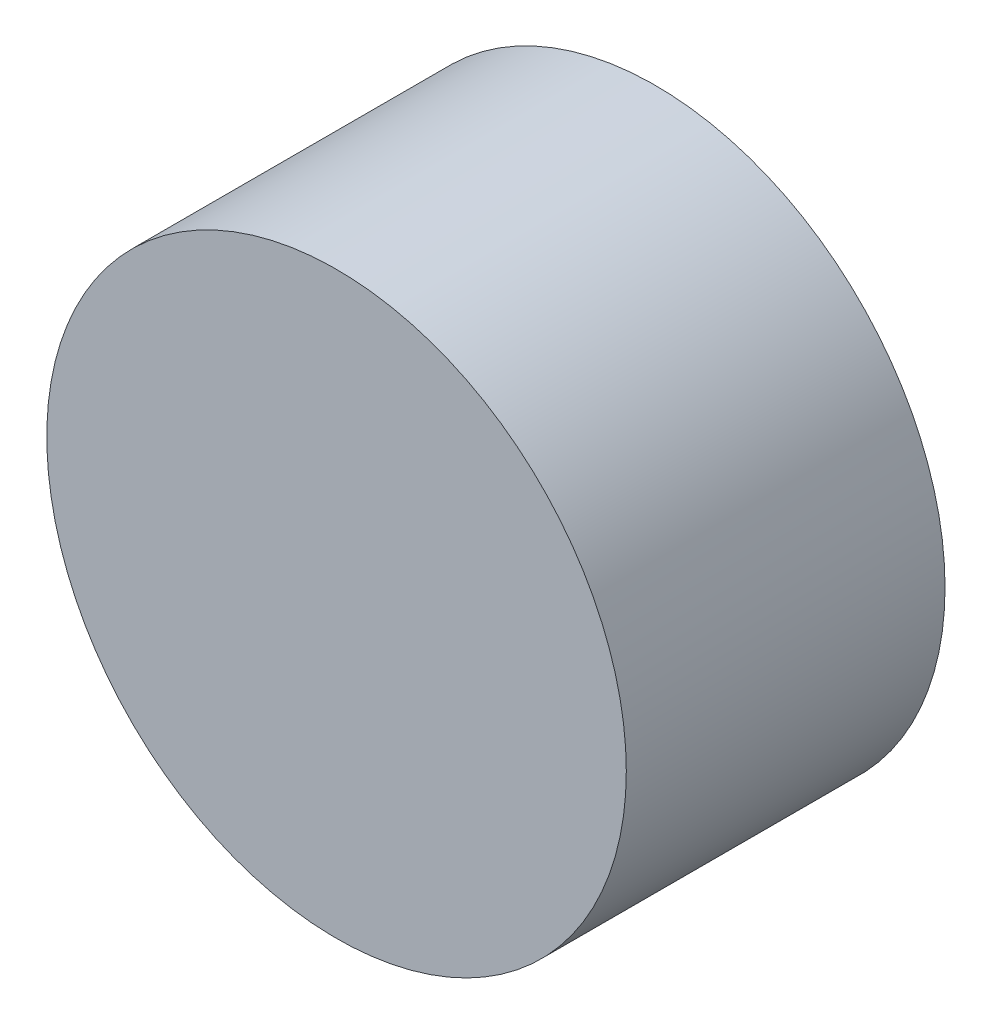
SolidWorks part; units mm, degrees
ref_plane "Front Plane" through (0, 0, 0) normal (0, 0, 1) x (1, 0, 0)
ref_plane "Top Plane" through (0, 0, 0) normal (0, 1, 0) x (1, 0, 0)
ref_plane "Right Plane" through (0, 0, 0) normal (1, 0, 0) x (0, 0, -1)
sketch "Sketch1" plane through (0, 0, 0) normal (0, 0, 1) x (1, 0, 0)
  circle A0 centre (0, 0) radius 5
  dimension "D1" = 10
extrude "Boss-Extrude1" add sketch "Sketch1" along normal blind 5.5
